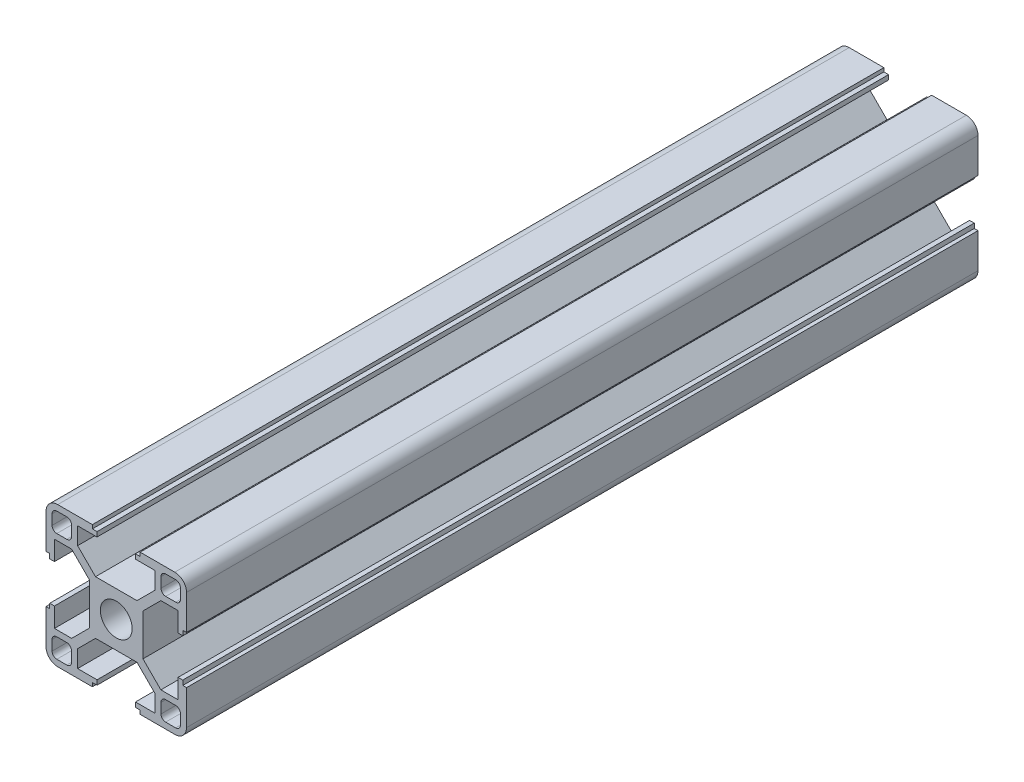
SolidWorks part; units mm, degrees
material "6061-T6 (SS)"
ref_plane "前视基准面" through (0, 0, 0) normal (0, 0, 1) x (1, 0, 0)
ref_plane "上视基准面" through (0, 0, 0) normal (0, 1, 0) x (1, 0, 0)
ref_plane "右视基准面" through (0, 0, 0) normal (1, 0, 0) x (0, 0, -1)
sketch "Sketch1" plane through (0, 0, 0) normal (0, 0, 1) x (1, 0, 0)
  line L0 (-5.1, 15) -> (-5.1, 14.2)
  line L1 (-12.5, -15) -> (12.5, -15)
  line L2 (-15, -12.5) -> (-15, 12.5)
  line L3 (-12.5, 15) -> (12.5, 15)
  line L4 (15, -12.5) -> (15, 12.5)
  line L5 (-15, -15) -> (15, 15) construction
  line L6 (-15, 15) -> (15, -15) construction
  line L7 (-5.1, 14.2) -> (-4.1, 14.2)
  line L8 (-4.1, 14.2) -> (-4.1, 13.2)
  line L9 (-4.1, 13.2) -> (-8.25, 13.2)
  line L10 (-8.25, 13.2) -> (-8.25, 9.5228)
  line L11 (-8.25, 9.5228) -> (-4.4272, 5.7)
  line L12 (-4.4272, 5.7) -> (4.4272, 5.7)
  line L13 (-5.1, 15) -> (5.1, 15)
  line L14 (0, 15) -> (0, 5.7) construction
  line L15 (8.25, 9.5228) -> (4.4272, 5.7)
  line L16 (8.25, 13.2) -> (8.25, 9.5228)
  line L17 (4.1, 13.2) -> (8.25, 13.2)
  line L18 (4.1, 14.2) -> (4.1, 13.2)
  line L19 (5.1, 14.2) -> (4.1, 14.2)
  line L20 (5.1, 15) -> (5.1, 14.2)
  line L21 (15, 5.1) -> (14.2, 5.1)
  line L22 (14.2, 5.1) -> (14.2, 4.1)
  line L23 (14.2, 4.1) -> (13.2, 4.1)
  line L24 (13.2, 4.1) -> (13.2, 8.25)
  line L25 (13.2, 8.25) -> (9.5228, 8.25)
  line L26 (9.5228, 8.25) -> (5.7, 4.4272)
  line L27 (5.7, 4.4272) -> (5.7, -4.4272)
  line L28 (15, 5.1) -> (15, -5.1)
  line L29 (9.5228, -8.25) -> (5.7, -4.4272)
  line L30 (13.2, -8.25) -> (9.5228, -8.25)
  line L31 (13.2, -4.1) -> (13.2, -8.25)
  line L32 (14.2, -4.1) -> (13.2, -4.1)
  line L33 (14.2, -5.1) -> (14.2, -4.1)
  line L34 (15, -5.1) -> (14.2, -5.1)
  line L35 (15, 0) -> (5.7, 0) construction
  line L36 (5.1, -15) -> (5.1, -14.2)
  line L37 (5.1, -14.2) -> (4.1, -14.2)
  line L38 (4.1, -14.2) -> (4.1, -13.2)
  line L39 (4.1, -13.2) -> (8.25, -13.2)
  line L40 (8.25, -13.2) -> (8.25, -9.5228)
  line L41 (8.25, -9.5228) -> (4.4272, -5.7)
  line L42 (4.4272, -5.7) -> (-4.4272, -5.7)
  line L43 (5.1, -15) -> (-5.1, -15)
  line L44 (-8.25, -9.5228) -> (-4.4272, -5.7)
  line L45 (-8.25, -13.2) -> (-8.25, -9.5228)
  line L46 (-4.1, -13.2) -> (-8.25, -13.2)
  line L47 (-4.1, -14.2) -> (-4.1, -13.2)
  line L48 (-5.1, -14.2) -> (-4.1, -14.2)
  line L49 (-5.1, -15) -> (-5.1, -14.2)
  line L50 (0, -15) -> (0, -5.7) construction
  line L51 (-15, -5.1) -> (-14.2, -5.1)
  line L52 (-14.2, -5.1) -> (-14.2, -4.1)
  line L53 (-14.2, -4.1) -> (-13.2, -4.1)
  line L54 (-13.2, -4.1) -> (-13.2, -8.25)
  line L55 (-13.2, -8.25) -> (-9.5228, -8.25)
  line L56 (-9.5228, -8.25) -> (-5.7, -4.4272)
  line L57 (-5.7, -4.4272) -> (-5.7, 4.4272)
  line L58 (-15, -5.1) -> (-15, 5.1)
  line L59 (-9.5228, 8.25) -> (-5.7, 4.4272)
  line L60 (-13.2, 8.25) -> (-9.5228, 8.25)
  line L61 (-13.2, 4.1) -> (-13.2, 8.25)
  line L62 (-14.2, 4.1) -> (-13.2, 4.1)
  line L63 (-14.2, 5.1) -> (-14.2, 4.1)
  line L64 (-15, 5.1) -> (-14.2, 5.1)
  line L65 (-15, 0) -> (-5.7, 0) construction
  line L66 (0, 0) -> (0, 5.7) construction
  circle A0 centre (0, 0) radius 3.4
  arc A1 (-12.5, -15) -> (-15, -12.5) centre (-12.5, -12.5) cw
  arc A2 (12.5, -15) -> (15, -12.5) centre (12.5, -12.5) ccw
  arc A3 (12.5, 15) -> (15, 12.5) centre (12.5, 12.5) cw
  arc A4 (-15, 12.5) -> (-12.5, 15) centre (-12.5, 12.5) cw
  point P0 (0, 0)
  dimension "D3" = 6.8
  dimension "D12" = 2.5
  dimension "D1" = 30
  dimension "D2" = 30
  dimension "D4" = 16.5
  dimension "D5" = 8.2
  dimension "D6" = 10.2
  dimension "D7" = 7.5
  dimension "D9" = 1.8
  dimension "D10" = 1.8
  dimension "D11" = 0.8
  dimension "D8" = 4
extrude "Extrude1" add sketch "Sketch1" along normal blind 169 contours A4 L2 L64 L63 L62 L61 L60 L59 L57 L56 L55 L54 L53 L52 L51 A1 L1 L49 L48 L47 L46 L45 L44 L42 L41 L40 L39 L38 L37 L36 A2 L4 L34 L33 L32 L31 L30 L29 L27 L26 L25 L24 L23 L22 L21 A3 L3 L20
sketch "Sketch2" plane through (0, 0, 169) normal (0, 0, 1) x (1, 0, 0)
  line L0 (13.7, 12.7) -> (13.7, 10.55)
  line L1 (-12.7, 13.7) -> (-10.55, 13.7)
  line L2 (-13.7, 12.7) -> (-13.7, 10.55)
  line L3 (-12.7, 9.55) -> (-10.55, 9.55)
  line L4 (-9.55, 12.7) -> (-9.55, 10.55)
  line L5 (-13.7, 13.7) -> (-9.55, 9.55) construction
  line L6 (-13.7, 9.55) -> (-9.55, 13.7) construction
  line L7 (12.7, 13.7) -> (10.55, 13.7)
  line L8 (9.55, 12.7) -> (9.55, 10.55)
  line L9 (12.7, 9.55) -> (10.55, 9.55)
  line L10 (12.7, -13.7) -> (10.55, -13.7)
  line L11 (13.7, -12.7) -> (13.7, -10.55)
  line L12 (12.7, -9.55) -> (10.55, -9.55)
  line L13 (9.55, -12.7) -> (9.55, -10.55)
  line L14 (-13.7, -12.7) -> (-13.7, -10.55)
  line L15 (-12.7, -13.7) -> (-10.55, -13.7)
  line L16 (-9.55, -12.7) -> (-9.55, -10.55)
  line L17 (-12.7, -9.55) -> (-10.55, -9.55)
  line L18 (0, 0) -> (-9.55, 9.55) construction
  line L19 (-12.5, 15) -> (-5.1, 15) construction
  line L20 (-15, 5.1) -> (-15, 12.5) construction
  line L21 (-13.2, 8.25) -> (-9.5228, 8.25) construction
  line L22 (-8.25, 13.2) -> (-8.25, 9.5228) construction
  arc A0 (-13.7, -12.7) -> (-12.7, -13.7) centre (-12.7, -12.7) ccw
  arc A1 (-10.55, -13.7) -> (-9.55, -12.7) centre (-10.55, -12.7) ccw
  arc A2 (-9.55, -10.55) -> (-10.55, -9.55) centre (-10.55, -10.55) ccw
  arc A3 (-13.7, -10.55) -> (-12.7, -9.55) centre (-12.7, -10.55) cw
  arc A4 (13.7, -10.55) -> (12.7, -9.55) centre (12.7, -10.55) ccw
  arc A5 (12.7, -13.7) -> (13.7, -12.7) centre (12.7, -12.7) ccw
  arc A6 (10.55, -13.7) -> (9.55, -12.7) centre (10.55, -12.7) cw
  arc A7 (10.55, -9.55) -> (9.55, -10.55) centre (10.55, -10.55) ccw
  arc A8 (13.7, 12.7) -> (12.7, 13.7) centre (12.7, 12.7) ccw
  arc A9 (13.7, 10.55) -> (12.7, 9.55) centre (12.7, 10.55) cw
  arc A10 (9.55, 10.55) -> (10.55, 9.55) centre (10.55, 10.55) ccw
  arc A11 (10.55, 13.7) -> (9.55, 12.7) centre (10.55, 12.7) ccw
  arc A12 (-10.55, 13.7) -> (-9.55, 12.7) centre (-10.55, 12.7) cw
  arc A13 (-10.55, 9.55) -> (-9.55, 10.55) centre (-10.55, 10.55) ccw
  arc A14 (-13.7, 10.55) -> (-12.7, 9.55) centre (-12.7, 10.55) ccw
  arc A15 (-12.7, 13.7) -> (-13.7, 12.7) centre (-12.7, 12.7) ccw
  point P0 (-11.625, 11.625)
  dimension "D2" = 1
  dimension "D3" = 1.3
  dimension "D4" = 1.3
  dimension "D5" = 1.3
  dimension "D6" = 1.3
  dimension "D1" = 4
extrude "Extrude2" cut sketch "Sketch2" against normal through all
